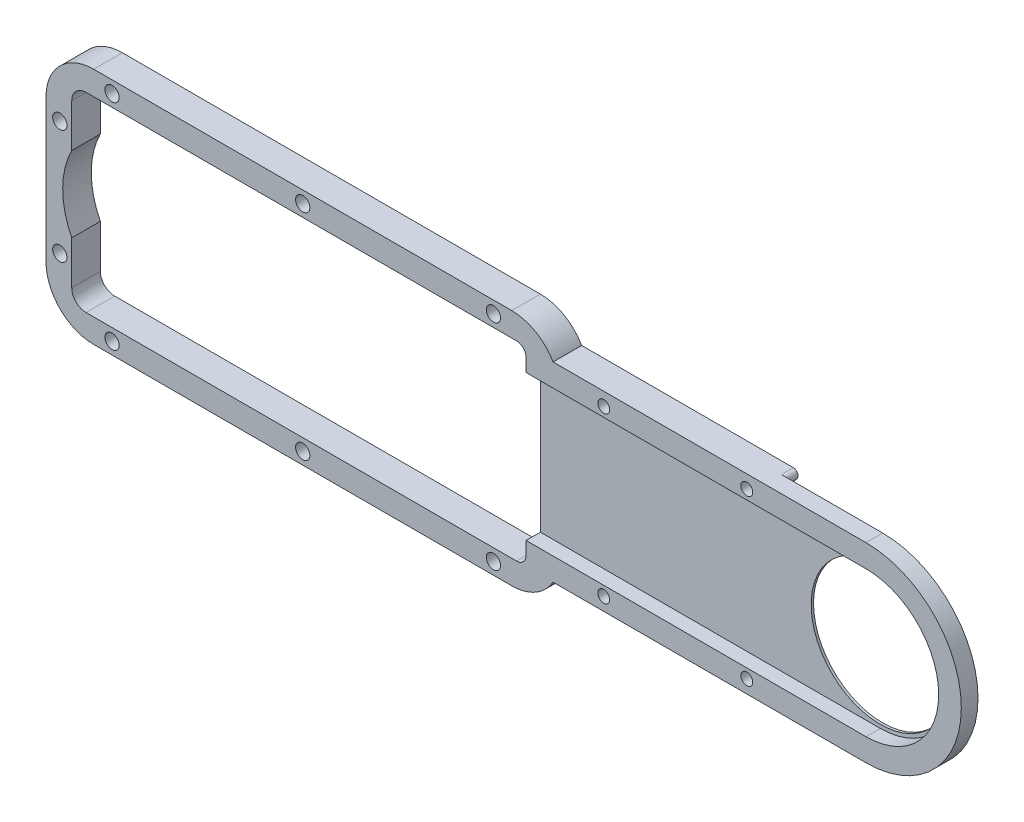
SolidWorks part; units mm, degrees
material "PET"
ref_plane "Front" through (0, 0, 0) normal (0, 0, 1) x (1, 0, 0)
ref_plane "Top" through (0, 0, 0) normal (0, 1, 0) x (1, 0, 0)
ref_plane "Right" through (0, 0, 0) normal (1, 0, 0) x (0, 0, -1)
ref_plane "Plane1" through (0, 0, 6) normal (0, 0, 1) x (1, 0, 0)
sketch "Sketch1" plane through (0, 0, 6) normal (0, 0, 1) x (1, 0, 0)
  line L0 (74.5699, 20.9449) -> (8.9301, 20.9449)
  line L1 (0.2699, 25.9449) -> (-97.4301, 25.9449)
  line L2 (-97.4301, 25.9449) -> (-97.4301, -24.0551)
  line L3 (-97.4301, -24.0551) -> (0.2699, -24.0551)
  line L4 (8.9301, -19.0551) -> (74.5699, -19.0551)
  arc A0 (74.5699, -19.0551) -> (74.5699, 20.9449) centre (74.5699, 0.9449) ccw
  arc A1 (8.9301, 20.9449) -> (0.2699, 25.9449) centre (0.2699, 15.9449) ccw
  arc A2 (0.2699, -24.0551) -> (8.9301, -19.0551) centre (0.2699, -14.0551) ccw
extrude "Boss-Extrude1" add sketch "Sketch1" against normal blind 6
sketch "Sketch2" plane through (0, 0, 0) normal (0, 0, -1) x (-1, 0, 0)
  line L0 (92.0301, 20.9449) -> (-3.2699, 20.9449)
  line L1 (-3.2699, 20.9449) -> (-3.2699, -19.0551)
  line L2 (-3.2699, -19.0551) -> (92.0301, -19.0551)
  line L3 (92.0301, -19.0551) -> (92.0301, -6.9854)
  line L4 (92.0301, 8.8752) -> (92.0301, 20.9449)
  arc A0 (92.0301, -6.9854) -> (92.0301, 8.8752) centre (76.4301, 0.9449) ccw
extrude "Cut-Extrude1" cut sketch "Sketch2" against normal through all
sketch "Sketch3" plane through (0, 0, 6) normal (0, 0, 1) x (1, 0, 0)
  line L0 (74.5699, 16.1949) -> (3.2699, 16.1949)
  line L1 (3.2699, 16.1949) -> (3.2699, -14.3051)
  line L2 (3.2699, -14.3051) -> (74.5699, -14.3051)
  arc A0 (74.5699, -14.3051) -> (74.5699, 16.1949) centre (74.5699, 0.9449) ccw
extrude "Cut-Extrude2" cut sketch "Sketch3" against normal blind 3
hole_wizard "#2 Clearance Hole1" positions "Sketch5" profile "Sketch4" hole size "#2" standard "ANSI Inch"
sketch "Sketch5" plane through (0, 0, 6) normal (0, 0, 1) x (1, 0, 0)
  point P2 (49.5699, 18.1949)
  point P3 (19.5699, -16.3051)
  point P4 (19.5699, 18.1949)
  point P5 (49.5699, -16.3051)
sketch "Sketch4" plane through (49.5699, 18.1949, 6) normal (1, 0, 0) x (0, -1, 0)
  line L0 (0, 0) -> (0, 6)
  line L1 (0, 6) -> (1.25, 6)
  line L2 (1.25, 6) -> (1.25, 0)
  line L5 (1.25, 0) -> (0, 0)
  line L11 (0, -6.35) -> (0, 107.95) construction
  dimension "Thru Hole Dia." = 2.5
  dimension "Thru Hole Depth" = 6
hole_wizard "1-1/8 Clearance Hole1" positions "Sketch7" profile "Sketch6" hole size "1-1/8" standard "ANSI Inch"
sketch "Sketch7" plane through (0, 0, 3) normal (0, 0, 1) x (1, 0, 0)
  point P0 (74.5699, 0.9449)
sketch "Sketch6" plane through (74.5699, 0.9449, 3) normal (1, 0, 0) x (0, -1, 0)
  line L0 (0, 0) -> (0, 3)
  line L1 (0, 3) -> (14.5, 3)
  line L2 (14.5, 3) -> (14.5, 0)
  line L5 (14.5, 0) -> (0, 0)
  line L11 (0, -6.35) -> (0, 107.95) construction
  dimension "Thru Hole Dia." = 29
  dimension "Thru Hole Depth" = 3
hole_wizard "#3 Clearance Hole1" positions "Sketch9" profile "Sketch8" hole size "#3" standard "ANSI Inch"
sketch "Sketch9" plane through (0, 0, 6) normal (0, 0, 1) x (1, 0, 0)
  point P0 (-3.5801, 23.4449)
  point P1 (-43.5801, 23.4449)
  point P2 (-83.5801, 23.4449)
  point P3 (-94.5301, 12.9449)
  point P4 (-94.5301, -11.0551)
  point P5 (-43.5801, -21.5551)
  point P6 (-3.5801, -21.5551)
  point P7 (-83.5801, -21.5551)
sketch "Sketch8" plane through (-3.5801, 23.4449, 6) normal (1, 0, 0) x (0, -1, 0)
  line L0 (0, 0) -> (0, 6)
  line L1 (0, 6) -> (1.5, 6)
  line L2 (1.5, 6) -> (1.5, 0)
  line L5 (1.5, 0) -> (0, 0)
  line L11 (0, -6.35) -> (0, 107.95) construction
  dimension "Thru Hole Dia." = 3
  dimension "Thru Hole Depth" = 6
fillet "Fillet1" radius 2 2 edges at (3.2699, 20.9449, 3) (3.2699, -19.0551, 3)
fillet "Fillet2" radius 3 2 edges at (-92.0301, 20.9449, 3) (-92.0301, -19.0551, 3)
fillet "Fillet3" radius 10 2 edges at (-97.4301, 25.9449, 3) (-97.4301, -24.0551, 3)
sketch "Sketch10" plane through (0, 0, 0) normal (0, 0, -1) x (-1, 0, 0)
  circle A0 centre (-74.5699, 0.9449) radius 27.5
  dimension "D3" = 55
extrude "Cut-Extrude3" cut sketch "Sketch10" against normal blind 2.5
fillet "Fillet4" radius 1 2 edges at (55.6953, -19.0551, 1.25) (55.6953, 20.9449, 1.25)
